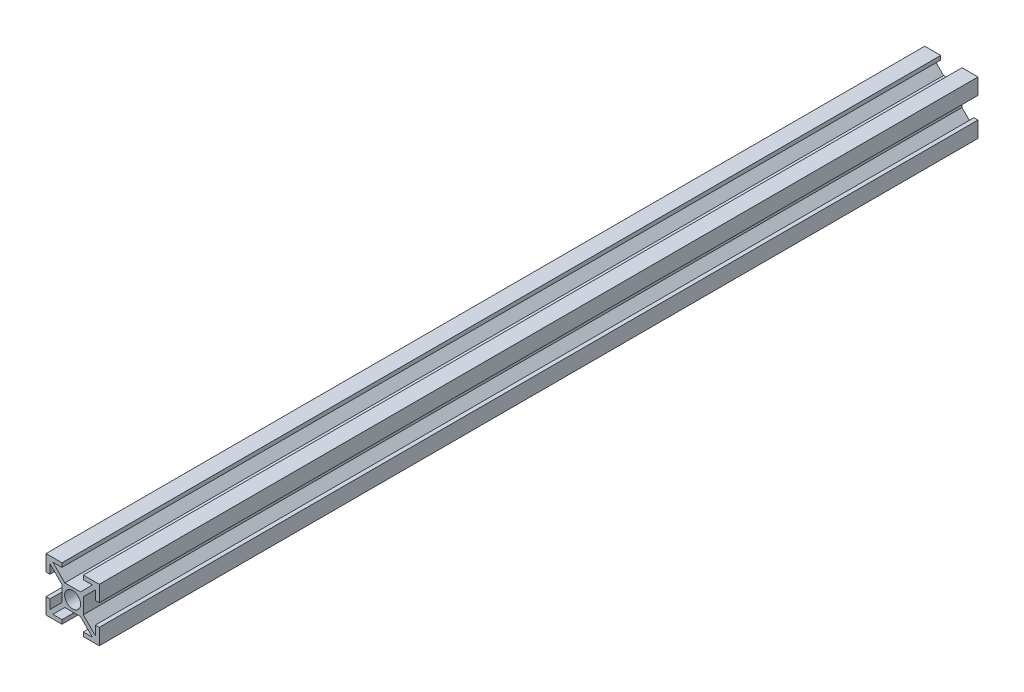
SolidWorks part; units mm, degrees
ref_plane "Plano frontal" through (0, 0, 0) normal (0, 0, 1) x (1, 0, 0)
ref_plane "Plano superior" through (0, 0, 0) normal (0, 1, 0) x (1, 0, 0)
ref_plane "Plano direito" through (0, 0, 0) normal (1, 0, 0) x (0, 0, -1)
sketch "Esboço1" plane through (0, 0, 0) normal (0, 0, 1) x (1, 0, 0)
  line L0 (-2.9393, 4) -> (2.9393, 4)
  line L1 (-10, -10) -> (-4, -10)
  line L2 (-10, -10) -> (-10, -4)
  line L3 (-10, 10) -> (-4, 10)
  line L4 (10, -10) -> (10, -4)
  line L5 (-10, -10) -> (-4, -4) construction
  line L6 (-10, 10) -> (0, 0) construction
  line L7 (-7.4393, -8.5) -> (-2.9393, -4)
  line L8 (4, -10) -> (10, -10)
  line L9 (-8.5, -7.4393) -> (-4, -2.9393)
  line L10 (-8.5, 7.4393) -> (-4, 2.9393)
  line L11 (-7.4393, -8.5) -> (-4, -8.5)
  line L12 (-8.5, -7.4393) -> (-8.5, -4)
  line L13 (-7.4393, 8.5) -> (-4, 8.5)
  line L14 (8.5, -7.4393) -> (8.5, -4)
  line L17 (-4, 10) -> (-4, 8.5)
  line L18 (4, -8.5) -> (7.4393, -8.5)
  line L19 (-10, -4) -> (-8.5, -4)
  line L20 (4, 10) -> (4, 8.5)
  line L21 (-10, 4) -> (-8.5, 4)
  line L22 (-4, 2.9393) -> (-4, -2.9393)
  line L23 (-4, -8.5) -> (-4, -10)
  line L24 (-8.5, 4) -> (-8.5, 7.4393)
  line L25 (-10, 4) -> (-10, 10)
  line L26 (-7.4393, 8.5) -> (-2.9393, 4)
  line L27 (4, 8.5) -> (7.4393, 8.5)
  line L28 (-2.9393, -4) -> (2.9393, -4)
  line L29 (4, 10) -> (10, 10)
  line L30 (4, -8.5) -> (4, -10)
  line L31 (10, 4) -> (10, 10)
  line L32 (8.5, 4) -> (8.5, 7.4393)
  line L33 (-10.5303, -9.4697) -> (9.4697, 10.5303) construction
  line L34 (8.5, 4) -> (10, 4)
  line L35 (8.5, -4) -> (10, -4)
  line L36 (-10, -10) -> (10, 10) construction
  line L37 (4, 2.9393) -> (4, -2.9393)
  line L38 (-9.4697, -10.5303) -> (10.5303, 9.4697) construction
  line L40 (2.9393, -4) -> (7.4393, -8.5)
  line L41 (4, -4) -> (10, -10) construction
  line L43 (4, -2.9393) -> (8.5, -7.4393)
  line L44 (4, 0) -> (10, 0) construction
  line L45 (4, 2.9393) -> (8.5, 7.4393)
  line L47 (4, 4) -> (10, 10) construction
  line L48 (2.9393, 4) -> (7.4393, 8.5)
  circle A0 centre (0, 0) radius 3
  point P0 (0, 0)
  point P14 (-4.0323, -3.9672)
  dimension "D5" = 6
  dimension "D1" = 0.75
  dimension "D3" = 1.5
  dimension "D4" = 20
  dimension "D6" = 8
  dimension "D7" = 20
  dimension "D9" = 1.5
  dimension "D2" = 8
extrude "Ressalto-extrusão1" add sketch "Esboço1" along normal blind 330
